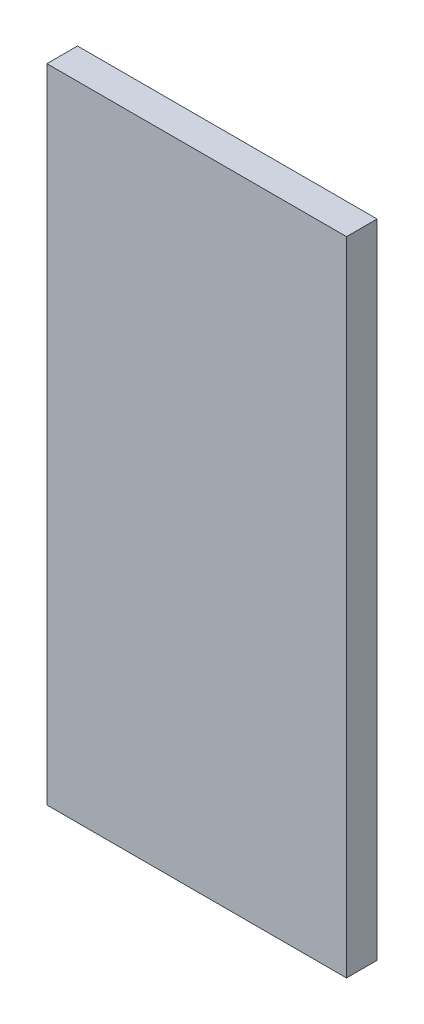
SolidWorks part; units mm, degrees
ref_plane "前视基准面" through (0, 0, 0) normal (0, 0, 1) x (1, 0, 0)
ref_plane "上视基准面" through (0, 0, 0) normal (0, 1, 0) x (1, 0, 0)
ref_plane "右视基准面" through (0, 0, 0) normal (1, 0, 0) x (0, 0, -1)
sketch "草图1" plane through (0, 0, 0) normal (0, 0, 1) x (1, 0, 0)
  line L1 (-98, 210) -> (98, 210)
  line L2 (-98, 210) -> (-98, -210)
  line L3 (-98, -210) -> (98, -210)
  line L4 (98, 210) -> (98, -210)
  line L5 (-98, 210) -> (98, -210) construction
  line L6 (-98, -210) -> (98, 210) construction
  point P0 (0, 0)
  dimension "D1" = 196
  dimension "D2" = 420
extrude "凸台-拉伸1" add sketch "草图1" along normal blind 20
